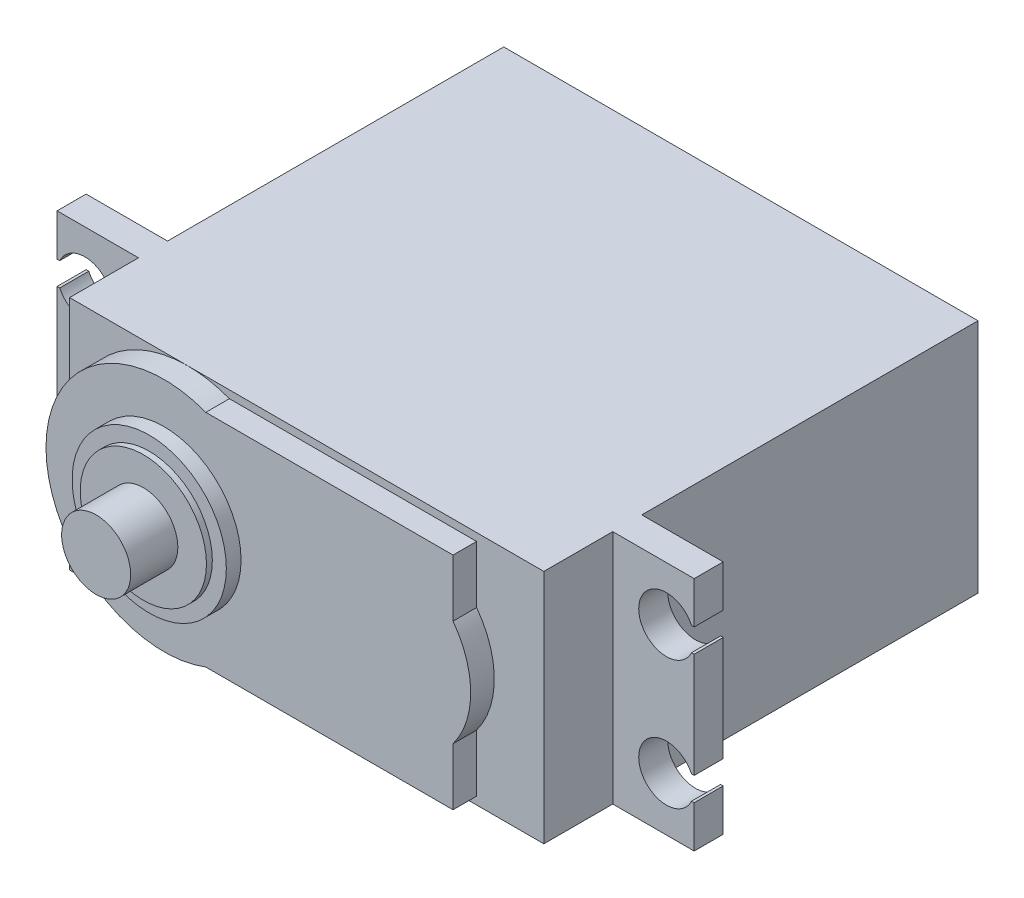
SolidWorks part; units mm, degrees
ref_plane "Ebene vorne" through (0, 0, 0) normal (0, 0, 1) x (1, 0, 0)
ref_plane "Ebene oben" through (0, 0, 0) normal (0, 1, 0) x (1, 0, 0)
ref_plane "Ebene rechts" through (0, 0, 0) normal (1, 0, 0) x (0, 0, -1)
sketch "Skizze1" plane through (0, 0, 0) normal (0, 1, 0) x (1, 0, 0)
  line L1 (-20.1, -18.4) -> (20.1, -18.4)
  line L2 (-20.1, -18.4) -> (-20.1, 18.4)
  line L3 (-20.1, 18.4) -> (20.1, 18.4)
  line L4 (20.1, -18.4) -> (20.1, 18.4)
  line L5 (-20.1, -18.4) -> (20.1, 18.4) construction
  line L6 (-20.1, 18.4) -> (20.1, -18.4) construction
  point P0 (0, 0)
  dimension "D1" = 40.2
  dimension "D2" = 36.8
extrude "Aufsatz-Linear austragen1" add sketch "Skizze1" along normal blind 20
sketch "Skizze2" plane through (0, 0, 18.4) normal (0, 0, 1) x (1, 0, 0)
  line L0 (0, -11) -> (0, 11) construction
  line L3 (-6.5535, 19.35) -> (14.4, 19.35)
  line L4 (14.4, 0.65) -> (14.4, 5.5)
  line L5 (-14.1092, 0.8388) -> (0.924, 10.6) construction
  line L6 (-14.1092, 19.1612) -> (0, 10) construction
  line L7 (20.1, 20) -> (20.1, 0) construction
  line L8 (-20.1, 20) -> (20.1, 20) construction
  line L10 (-6.5535, 0.65) -> (14.4, 0.65)
  line L11 (-20.1, 20) -> (-20.1, 0) construction
  line L12 (15.9, 10) -> (15.9, 1.2074) construction
  line L13 (10.8937, 17.0733) -> (14.4, 19.35) construction
  line L14 (10.8937, 2.9267) -> (14.4, 0.65) construction
  line L15 (14.4, 14.5) -> (14.4, 19.35)
  arc A0 (-0.1002, 9.9349) -> (-0.1002, 10.0651) centre (-10.1, 10) ccw
  arc A2 (14.4, 5.5) -> (14.4, 14.5) centre (8.4, 10) ccw
  arc A3 (-6.5535, 19.35) -> (-6.5535, 0.65) centre (-10.1, 10) ccw
  point P0 (0, 10)
  point P21 (14.4, 14.5)
  point P22 (14.4, 5.5)
  dimension "D4" = 20
  dimension "D5" = 10
  dimension "D6" = 36
  dimension "D1" = 5.7
  dimension "D2" = 0.65
  dimension "D7" = 9
extrude "Aufsatz-Linear austragen2" add sketch "Skizze2" along normal blind 2
sketch "Skizze3" plane through (0, 0, 20.4) normal (0, 0, 1) x (1, 0, 0)
  line L0 (-10.1, 20) -> (-10.1, 0) construction
  line L1 (21.34, 0) -> (-21.34, 0) construction
  line L2 (-10.1, 0) -> (-20.1, 10) construction
  line L3 (-20.1, 10) -> (-10.1, 10) construction
  arc A0 (-6.5535, 19.35) -> (-6.5535, 0.65) centre (-10.1, 10) ccw construction
  circle A1 centre (-10.1, 10) radius 6.535
  dimension "D1" = 13.07
extrude "Aufsatz-Linear austragen3" add sketch "Skizze3" along normal blind 1.25
sketch "Skizze4" plane through (0, 0, 21.65) normal (0, 0, 1) x (1, 0, 0)
  line L0 (-16.635, 10) -> (-3.565, 10) construction
  line L1 (-3.565, 10) -> (-10.1, 16.535) construction
  circle A0 centre (-10.1, 10) radius 6.535 construction
  circle A1 centre (-10.1, 10) radius 6.535 construction
  circle A2 centre (-10.1, 10) radius 5.35
  dimension "D1" = 10.7
extrude "Aufsatz-Linear austragen4" add sketch "Skizze4" along normal blind 0.5
sketch "Skizze5" plane through (0, 0, 22.15) normal (0, 0, 1) x (1, 0, 0)
  line L0 (-4.75, 10) -> (-15.45, 10) construction
  line L1 (-15.45, 10) -> (-10.1, 15.35) construction
  circle A0 centre (-10.1, 10) radius 5.35 construction
  circle A1 centre (-10.1, 10) radius 5.35 construction
  circle A2 centre (-10.1, 10) radius 2.925
  dimension "D1" = 5.85
extrude "Aufsatz-Linear austragen5" add sketch "Skizze5" along normal blind 4
ref_plane "Ebene1" through (0, 0, 10.1) normal (0, 0, -1) x (-1, 0, 0)
sketch "Skizze6" plane through (0, 0, 10.1) normal (0, 0, -1) x (-1, 0, 0)
  line L0 (20.1, 20) -> (20.1, 0)
  line L1 (20.1, 20) -> (27, 20)
  line L2 (20.1, 0) -> (27, 0)
  line L3 (27, 20) -> (27, 16.45)
  line L4 (22.11, 0) -> (-22.11, 0) construction
  line L5 (20.1, 20) -> (20.1, 0) construction
  line L6 (27, 3.55) -> (27, 0)
  line L7 (24.65, 2.2) -> (26.658, 2.2) construction
  line L8 (24.65, 17.8) -> (26.447, 17.8) construction
  line L9 (0, 11) -> (0, -11) construction
  line L10 (27, 14.45) -> (27, 5.55)
  line L11 (27, 3.55) -> (26.7766, 3.55)
  line L13 (27, 5.55) -> (26.7766, 5.55)
  line L15 (-27, 3.55) -> (-27, 0)
  line L16 (-20.1, 0) -> (-27, 0)
  line L17 (27, 14.45) -> (26.7766, 14.45)
  line L19 (27, 16.45) -> (26.7766, 16.45)
  line L21 (-20.1, 20) -> (-20.1, 0)
  line L22 (-20.1, 20) -> (-27, 20)
  line L23 (-27, 20) -> (-27, 16.45)
  line L24 (-27, 16.45) -> (-26.7766, 16.45)
  line L25 (-27, 14.45) -> (-26.7766, 14.45)
  line L26 (-27, 14.45) -> (-27, 5.55)
  line L27 (-27, 5.55) -> (-26.7766, 5.55)
  line L28 (-27, 3.55) -> (-26.7766, 3.55)
  arc A2 (26.7766, 5.55) -> (26.7766, 3.55) centre (24.65, 4.55) ccw
  arc A3 (26.7766, 16.45) -> (26.7766, 14.45) centre (24.65, 15.45) ccw
  arc A4 (-26.7766, 16.45) -> (-26.7766, 14.45) centre (-24.65, 15.45) cw
  arc A5 (-26.7766, 5.55) -> (-26.7766, 3.55) centre (-24.65, 4.55) cw
  dimension "D2" = 2.2
  dimension "D3" = 2.2
  dimension "D6" = 4.7
  dimension "D7" = 4.7
  dimension "D1" = 6.9
  dimension "D4" = 2.35
  dimension "D5" = 2.35
extrude "Aufsatz-Linear austragen6" add sketch "Skizze6" against normal blind 2.46
